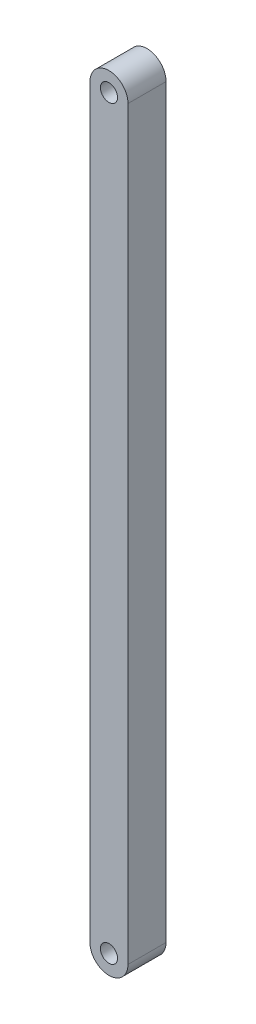
SolidWorks part; units mm, degrees
material "Papel canelado"
ref_plane "Plano frontal" through (0, 0, 0) normal (0, 0, 1) x (1, 0, 0)
ref_plane "Plano superior" through (0, 0, 0) normal (0, 1, 0) x (1, 0, 0)
ref_plane "Plano direito" through (0, 0, 0) normal (1, 0, 0) x (0, 0, -1)
sketch "Esboço1" plane through (0, 0, 0) normal (0, 0, 1) x (1, 0, 0)
  line L0 (0, 195.85) -> (0, 0) construction
  line L1 (5, 195.85) -> (5, 0)
  line L2 (-5, 195.85) -> (-5, 0)
  circle A0 centre (0, 0) radius 2.25
  circle A1 centre (0, 195.85) radius 2.25
  arc A2 (5, 195.85) -> (-5, 195.85) centre (0, 195.85) ccw
  arc A3 (-5, 0) -> (5, 0) centre (0, 0) ccw
  point P5 (0, 97.925)
  dimension "D1" = 195.85
  dimension "D2" = 4.5
  dimension "D3" = 10
extrude "Ressalto-extrusão1" add sketch "Esboço1" along normal blind 10
